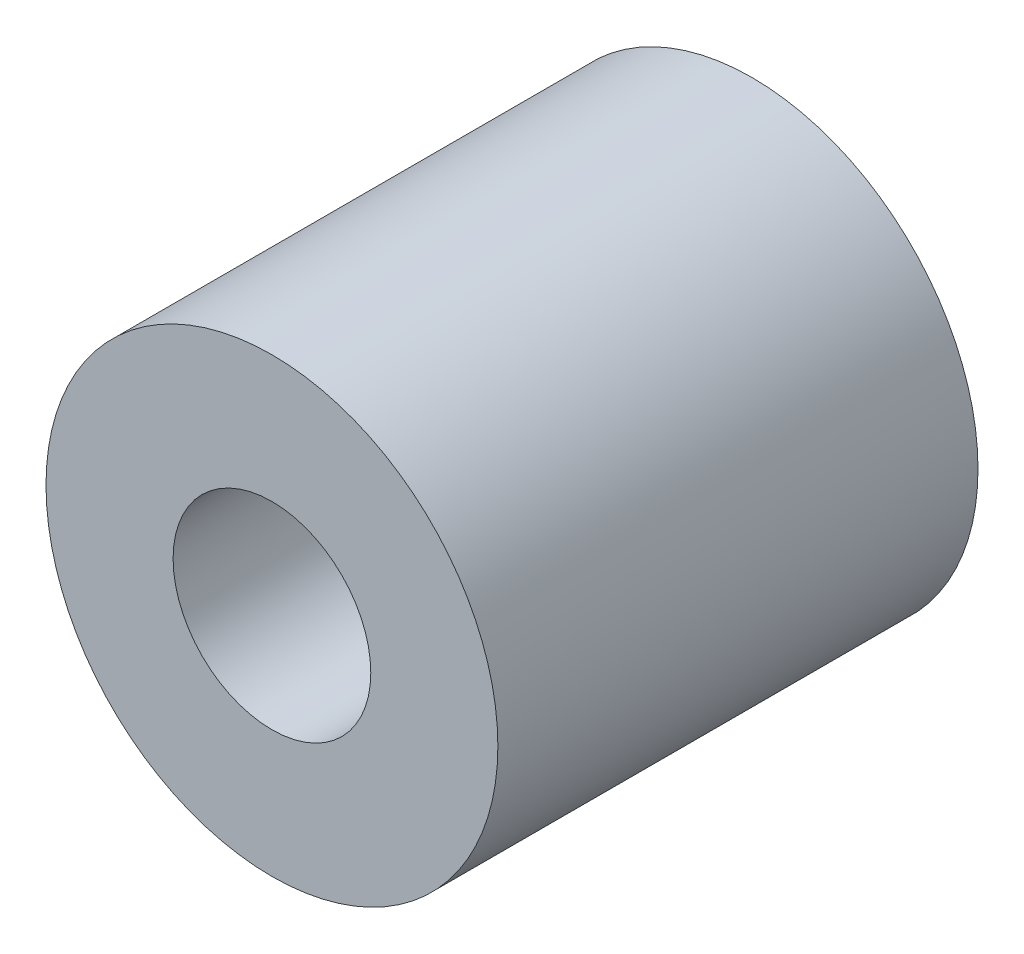
SolidWorks part; units mm, degrees
material "PLA"
ref_plane "前视基准面" through (0, 0, 0) normal (0, 0, 1) x (1, 0, 0)
ref_plane "上视基准面" through (0, 0, 0) normal (0, 1, 0) x (1, 0, 0)
ref_plane "右视基准面" through (0, 0, 0) normal (1, 0, 0) x (0, 0, -1)
other "Configuration Table"
sketch "草图1" plane through (0, 0, 0) normal (0, 0, 1) x (1, 0, 0)
  circle A0 centre (0, 0) radius 1.75
  circle A1 centre (0, 0) radius 4
  dimension "D1" = 8
  dimension "D2" = 3.5
extrude "凸台-拉伸1" add sketch "草图1" along normal blind 8.5
